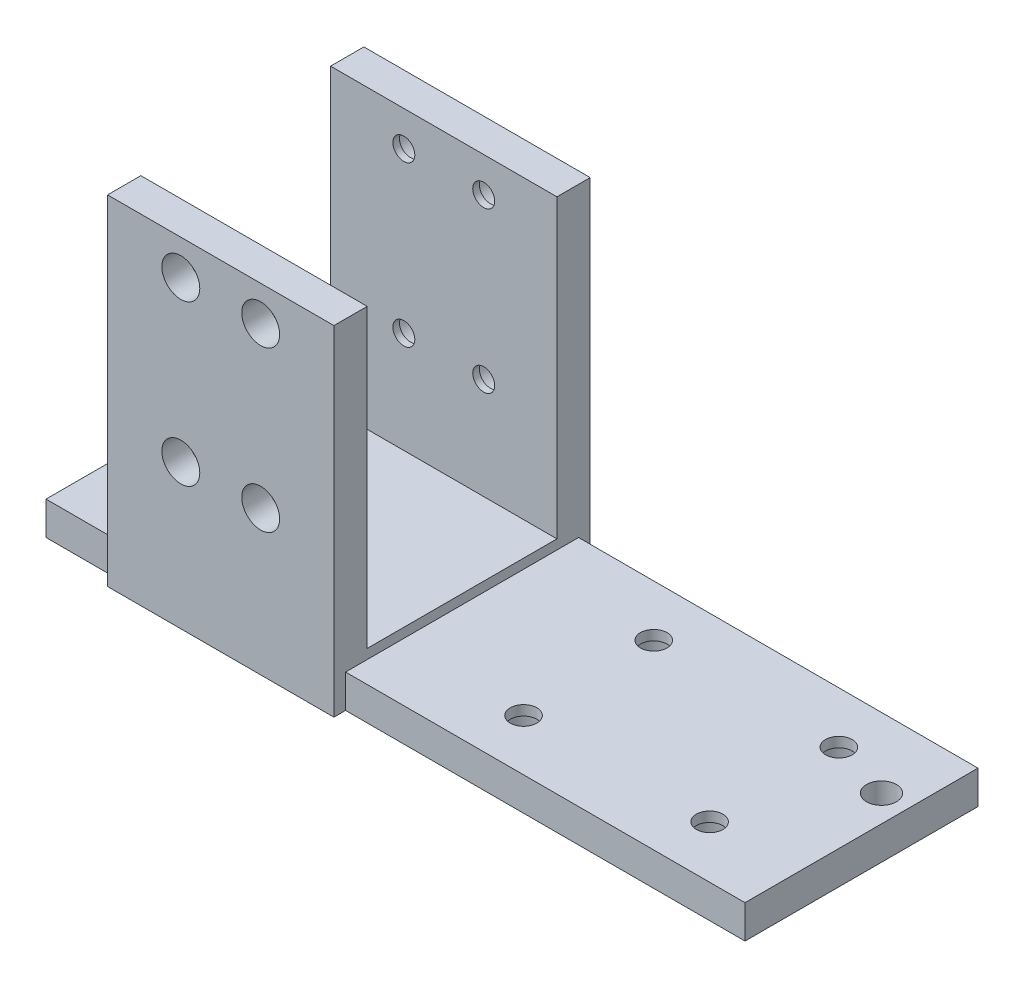
SolidWorks part; units mm, degrees
material "ABS"
ref_plane "Front Plane" through (0, 0, 0) normal (0, 0, 1) x (1, 0, 0)
ref_plane "Top Plane" through (0, 0, 0) normal (0, 1, 0) x (1, 0, 0)
ref_plane "Right Plane" through (0, 0, 0) normal (1, 0, 0) x (0, 0, -1)
sketch "Sketch1" plane through (0, 0, 0) normal (0, 1, 0) x (1, 0, 0)
  line L1 (-52.5, -17.5) -> (52.5, -17.5)
  line L2 (-52.5, -17.5) -> (-52.5, 17.5)
  line L3 (-52.5, 17.5) -> (52.5, 17.5)
  line L4 (52.5, -17.5) -> (52.5, 17.5)
  line L5 (-52.5, -17.5) -> (52.5, 17.5) construction
  line L6 (-52.5, 17.5) -> (52.5, -17.5) construction
  point P0 (0, 0)
  dimension "D1" = 35
  dimension "D2" = 105
extrude "Boss-Extrude1" add sketch "Sketch1" along normal blind 5
hole_wizard "M4 Clearance Hole1" positions "Sketch2" profile "Sketch3" hole size "M4" standard "ANSI Metric" end condition through all
sketch "Sketch2" plane through (0, 5, 0) normal (0, 1, 0) x (1, 0, 0)
  line L0 (-52.5, 17.5) -> (-52.5, -17.5) construction
  line L1 (52.5, -17.5) -> (52.5, 17.5) construction
  line L3 (52.5, 17.5) -> (-52.5, 17.5) construction
  point P0 (-48.5, 7)
  point P2 (48.5, 7)
  point P19 (0, 0)
  dimension "D1" = 4
  dimension "D2" = 4
  dimension "D3" = 10.5
sketch "Sketch3" plane through (-48.5, 5, -7) normal (1, 0, 0) x (0, 0, 1)
  line L0 (0, 0) -> (0, 5)
  line L1 (0, 5) -> (2.25, 5)
  line L2 (2.25, 5) -> (2.25, 0)
  line L5 (2.25, 0) -> (0, 0)
  line L11 (0, -6.35) -> (0, 107.95) construction
  dimension "Thru Hole Dia." = 4.5
  dimension "Thru Hole Depth" = 5
sketch "Sketch4" plane through (0, 5, 0) normal (0, 1, 0) x (1, 0, 0)
  line L0 (52.5, 17.5) -> (-52.5, 17.5) construction
  line L1 (-7.9, 17.5) -> (-41.1, 17.5)
  line L2 (-7.9, 17.5) -> (-7.9, -17.5)
  line L3 (-7.9, -17.5) -> (-41.1, -17.5)
  line L4 (-41.1, 17.5) -> (-41.1, -17.5)
  line L5 (-52.5, -17.5) -> (52.5, -17.5) construction
  line L6 (-7.9, -12.25) -> (-7.9, 12.25) construction
  line L7 (-41.1, 12.25) -> (-41.1, 3.5) construction
extrude "Boss-Extrude2" add sketch "Sketch4" along normal up to surface (1.45 mm away)
ref_plane "Plane1" through (-24.5, 0, 0) normal (-1, 0, 0) x (0, 0, 1)
sketch "Sketch5" plane through (-24.5, 0, 0) normal (-1, 0, 0) x (0, 0, 1)
  line L0 (-17.5, 0) -> (-19.25, 0)
  line L1 (-19.25, 0) -> (-19.25, 50.95)
  line L2 (-19.25, 50.95) -> (-14.25, 50.95)
  line L3 (-14.25, 50.95) -> (-14.25, 6.45)
  line L4 (-14.25, 6.45) -> (-17.5, 6.45)
  line L5 (-17.5, 6.45) -> (-17.5, 0)
  line L6 (-14.25, 50.95) -> (-14.25, 38.7) construction
  dimension "D1" = 5
extrude "Boss-Extrude3" add sketch "Sketch5" along normal up to surface (17 mm away) and the other way up to surface (17 mm away)
hole_wizard "CBORE for M2.5 SHCS1" positions "Sketch8" profile "Sketch9" counterbore size "M2.5" standard "ANSI Metric"
sketch "Sketch8" plane through (0, 0, -19.25) normal (0, 0, -1) x (-1, 0, 0)
  point P0 (30.5, 45.7)
  point P3 (18.5, 45.7)
  point P6 (30.5, 21.7)
  point P9 (18.5, 21.7)
sketch "Sketch9" plane through (-30.5, 45.7, -19.25) normal (1, 0, 0) x (0, 1, 0)
  line L0 (0, 0) -> (0, 34.4904)
  line L1 (0, 34.4904) -> (1.65, 33.499)
  line L2 (1.65, 33.499) -> (1.65, 4)
  line L3 (1.65, 4) -> (2.85, 4)
  line L4 (2.85, 4) -> (2.85, 0)
  line L5 (2.85, 0) -> (0, 0)
  line L10 (0, 34.4904) -> (-1.65, 33.499) construction
  line L11 (0, -6.35) -> (0, 107.95) construction
  dimension "Hole Dia." = 3.3
  dimension "Hole Depth" = 33.499
  dimension "C'Bore Dia." = 5.7
  dimension "C'Bore Depth" = 4
  dimension "Drill Angle" = 118
ref_plane "Plane2" through (0, 0, 0) normal (0, 0, -1) x (-1, 0, 0)
mirror "Mirror1" about plane through (0, 0, 0) normal (0, 0, -1) of "CBORE for M2.5 SHCS1", "Boss-Extrude3"
sketch "Sketch11" plane through (-7.9, 0, 0) normal (1, 0, 0) x (0, 0, -1)
  line L6 (17.5, 5) -> (17.5, 6.45)
  line L7 (17.5, 6.45) -> (14.25, 6.45)
  line L8 (14.25, 6.45) -> (-14.25, 6.45)
  line L9 (-14.25, 6.45) -> (-17.5, 6.45)
  line L10 (-17.5, 6.45) -> (-17.5, 5)
  line L11 (-17.5, 5) -> (17.5, 5)
  line L12 (17.5, 5) -> (17.5, 6.45)
  line L13 (17.5, 6.45) -> (14.25, 6.45)
  line L14 (14.25, 6.45) -> (-14.25, 6.45)
  line L15 (-14.25, 6.45) -> (-17.5, 6.45)
  line L16 (-17.5, 6.45) -> (-17.5, 5)
  line L17 (-17.5, 5) -> (17.5, 5)
  dimension "D1" = 0
extrude "Boss-Extrude5" add sketch "Sketch11" along normal up to surface (0.4 mm away) up to face at (-7.5, 17.1143, 17.0714)
sketch "Sketch12" plane through (-41.1, 0, 0) normal (-1, 0, 0) x (0, 0, 1)
  line L6 (17.5, 5) -> (17.5, 6.45)
  line L7 (17.5, 6.45) -> (14.25, 6.45)
  line L8 (14.25, 6.45) -> (-14.25, 6.45)
  line L9 (-14.25, 6.45) -> (-17.5, 6.45)
  line L10 (-17.5, 6.45) -> (-17.5, 5)
  line L11 (-17.5, 5) -> (17.5, 5)
  line L12 (17.5, 5) -> (17.5, 6.45)
  line L13 (17.5, 6.45) -> (14.25, 6.45)
  line L14 (14.25, 6.45) -> (-14.25, 6.45)
  line L15 (-14.25, 6.45) -> (-17.5, 6.45)
  line L16 (-17.5, 6.45) -> (-17.5, 5)
  line L17 (-17.5, 5) -> (17.5, 5)
  dimension "D1" = 0
extrude "Boss-Extrude6" add sketch "Sketch12" along normal up to surface (0.4 mm away) up to face at (-41.5, 17.1143, -17.0714)
hole_wizard "CBORE for #6 Socket Head Cap Screw1" positions "Sketch13" profile "Sketch14" counterbore size "#6" standard "ANSI Inch" end condition up to next
sketch "Sketch13" plane through (0, 0, 0) normal (0, -1, 0) x (-1, 0, 0)
  point P0 (-39.325, 9.779)
  point P2 (-11.514, 9.779)
  point P4 (-39.325, -9.6397)
  point P6 (-11.514, -9.779)
sketch "Sketch14" plane through (39.325, 0, -9.779) normal (1, 0, 0) x (0, 0, -1)
  line L0 (0, 0) -> (0, 5)
  line L1 (0, 5) -> (1.9987, 5)
  line L3 (1.9987, 5) -> (1.9987, 3.5052)
  line L4 (1.9987, 3.5052) -> (3.6725, 3.5052)
  line L5 (3.6725, 3.5052) -> (3.6725, 0)
  line L7 (3.6725, 0) -> (0, 0)
  line L11 (0, -6.35) -> (0, 107.95) construction
  dimension "Thru Hole Dia." = 3.9973
  dimension "Thru Hole Depth" = 5
  dimension "C'Bore Dia." = 7.345
  dimension "C'Bore Depth" = 3.5052
